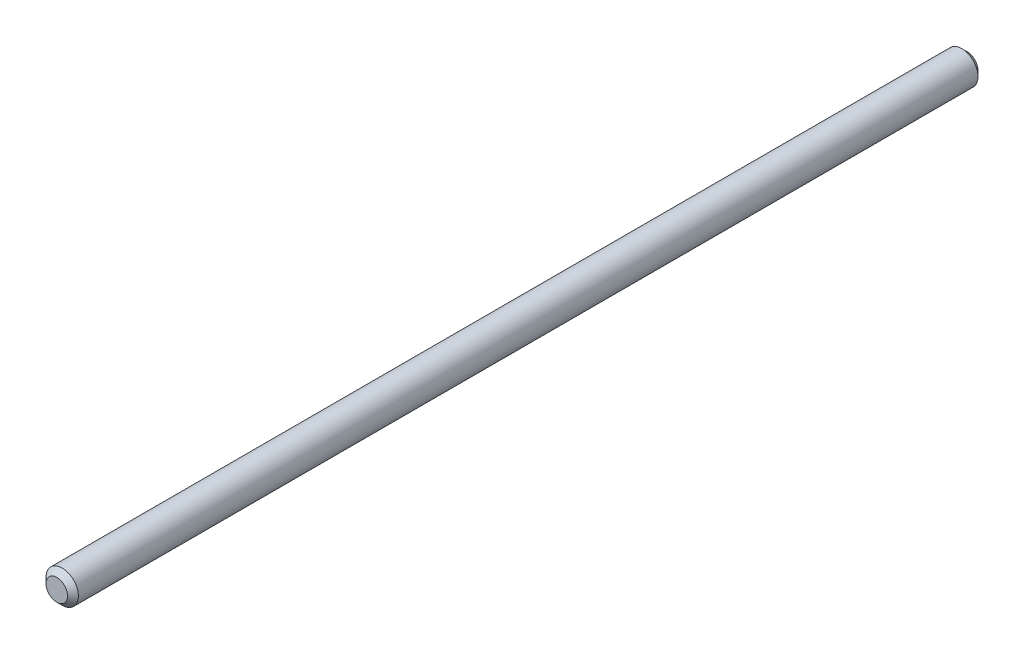
SolidWorks part; units mm, degrees
material "AISI 304"
ref_plane "Front Plane" through (0, 0, 0) normal (1, 0, 0) x (0, 1, 0)
ref_plane "Top Plane" through (0, 0, 0) normal (0, 0, 1) x (0, 1, 0)
ref_plane "Right Plane" through (0, 0, 0) normal (0, 1, 0) x (-1, 0, 0)
sketch "Sketch1" plane through (0, 0, 0) normal (0, 0, 1) x (0, 1, 0)
  circle A0 centre (0, 0) radius 1.5
  dimension "D1" = 3
extrude "Boss-Extrude1" add sketch "Sketch1" along normal blind 84.4 contours A0
chamfer "Chamfer1" distance 0.5 angle 45 2 edges at (1.5, 0, 84.4) (1.5, 0, 0)
